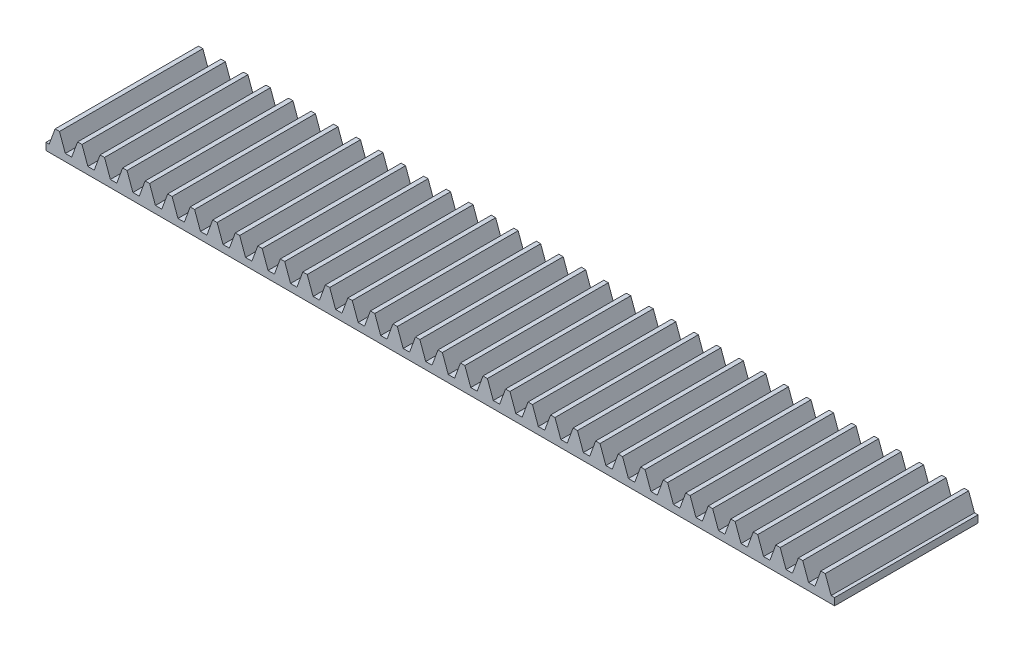
SolidWorks part; units mm, degrees
extrude "Blank" add sketch "BlankSke" against normal blind 20
sketch "BlankSke" plane through (0, 0, 0) normal (0, 0, 1) x (1, 0, 0)
  line L1 (0, 0) -> (110, 0)
  line L2 (0, 0) -> (0, 3.25)
  line L3 (0, 3.25) -> (110, 3.25)
  line L4 (110, 0) -> (110, 3.25)
  dimension "Length" = 110
  dimension "Blank_height" = 3.25
ref_plane "Plane1" through (0, 0, 0) normal (0, 0, 1) x (1, 0, 0)
ref_plane "Plane2" through (0, 0, 0) normal (0, 1, 0) x (1, 0, 0)
ref_plane "Plane3" through (0, 0, 0) normal (1, 0, 0) x (0, 0, -1)
other "Configuration Table"
sketch "HoldingSke" plane through (0, 0, 0) normal (0, 1, 0) x (1, 0, 0)
  line L0 (0, 0) -> (0.1392, 0.9903)
  line L1 (-15, 0) -> (100, 0) construction
  line L2 (0, 0) -> (-2.1039, 2.3779)
  line L3 (0, 0) -> (-11.863, 4.5341)
  line L4 (0, 0) -> (6.897, 5.1973)
  line L5 (0, 0) -> (-23.7986, -8.8762)
  line L6 (0, 0) -> (-10.5278, -7.1032)
  line L9 (-71.009, 38.7566) -> (32.3572, 76.3788)
  line L10 (-76.2, 3.3779) -> (-73.95, 3.3779)
  line L11 (0, 0) -> (-20, 0)
  line L12 (-76.2, 101.6) -> (-76.162, 101.6)
  line L13 (24.9733, 27.94) -> (52.9518, 28.4284)
  line L14 (24.9733, 27.94) -> (24.9743, 27.94)
  line L15 (24.9733, 27.94) -> (100.4006, 29.5858)
  circle A0 centre (0, 0) radius 19.05
  circle A1 centre (0, 0) radius 1.125
  circle A2 centre (0, 0) radius 12.7
  dimension "MPH" = 2.25
  dimension "Diameter" = 38.1
  dimension "Num_teeth" = 37
  dimension "Pitch" = 1
  dimension "Show_teeth" = 998
  dimension "Thickness" = 12.7
  dimension "Ap" = 20
  dimension "Pitch_height" = 2.25
  dimension "Width" = 20
  dimension "Backlash" = 0.038
  dimension "Addendum_fac" = 1
  dimension "Dedendum_fac" = 1.25
  dimension "Clearance_fac" = 0.25
  dimension "Dedendum_add" = 0.001
  dimension "Length" = 110
  dimension "Module" = 1
sketch "TooCutSkeIll" plane through (0, 0, 0) normal (0, 0, 1) x (1, 0, 0)
  line L0 (-1.2538, 3.2237) -> (-0.5045, 1.1652)
  line L1 (-0.2687, 1) -> (0.2687, 1)
  line L2 (0.5045, 1.1652) -> (1.2538, 3.2237)
  line L3 (110, 3.25) -> (0, 3.25) construction
  line L4 (0, 0) -> (0, 64.897) construction
  line L5 (-13.208, 2.25) -> (12.954, 2.25) construction
  line L6 (0, 0) -> (110, 0) construction
  line L7 (0.8994, 2.25) -> (0.8994, 48.7463) construction
  line L8 (-0.8994, 2.25) -> (-0.8994, 48.7463) construction
  line L9 (1.2914, 3.25) -> (1.2914, 3.2754)
  line L10 (-1.2914, 3.25) -> (-1.2914, 3.2754)
  line L11 (-1.2914, 3.2754) -> (1.2914, 3.2754)
  arc A0 (0.2687, 1) -> (0.5045, 1.1652) centre (0.2687, 1.251) ccw
  arc A1 (-0.5045, 1.1652) -> (-0.2687, 1) centre (-0.2687, 1.251) ccw
  arc A2 (1.2914, 3.25) -> (1.2538, 3.2237) centre (1.2914, 3.21) ccw
  arc A3 (-1.2538, 3.2237) -> (-1.2914, 3.25) centre (-1.2914, 3.21) ccw
  dimension "Pitch_height" = 2.25
  dimension "Addendum_plus" = 1.0254
  dimension "Pressure_angle" = 20
  dimension "Gap_width" = 1.7988
  dimension "Dedendum" = 1.25
extrude "ToothCutIll" [suppressed] cut sketch "TooCutSkeIll" against normal through all
sketch "TooCutSkeSim" plane through (0, 0, 0) normal (0, 0, 1) x (1, 0, 0)
  line L0 (0.4444, 1) -> (-0.4444, 1)
  line L1 (1.2726, 3.2754) -> (0.4444, 1)
  line L2 (0, 17.4625) -> (0, 53.467) construction
  line L3 (1.2726, 3.2754) -> (-1.2726, 3.2754)
  line L6 (-1.2726, 3.2754) -> (-0.4444, 1)
  line L9 (-0.8994, 2.25) -> (0.8994, 2.25) construction
  line L10 (0, 0) -> (110, 0) construction
  line L11 (0.8994, 2.25) -> (0.8994, 53.467) construction
  line L12 (-0.8994, 2.25) -> (-0.8994, 53.467) construction
  dimension "Pitch_height" = 2.25
  dimension "Addendum_plus" = 1.0254
  dimension "Pressure_angle" = 20
  dimension "Gap_width" = 1.7988
  dimension "Dedendum" = 1.25
extrude "ToothCutSim" cut sketch "TooCutSkeSim" against normal through all
pattern_linear "TeethCuts" count 36 spacing 3.1416 along (1, 0, 0) of "ToothCutIll", "ToothCutSim"
equation "' \"Module@HoldingSke\" = 6.35"
equation "' \"Num_teeth@HoldingSke\" = 12"
equation "' \"Ap@HoldingSke\" =  20"
equation "' \"Ap@HoldingSke\" = 20"
equation "' \"Width@HoldingSke\" = 0.25 * 25.4"
equation "' \"Show_teeth@HoldingSke\" = 500"
equation "' \"Backlash@HoldingSke\" = 0.009 * 25.4"
equation "' \"Addendum_fac@HoldingSke\" = 1.0"
equation "' \"Dedendum_fac@HoldingSke\" = 1.25"
equation "' \"Dedendum_add@HoldingSke\" = 0.00005 * 25.4"
equation "' \"Clearance_fac@HoldingSke\" = 0.25"
equation "' \"Pitch_height@HoldingSke\" = 1 * 25.4"
equation "' \"Length@HoldingSke\" = 4.71 * 25.4"
equation "\"Pitch@HoldingSke\" = 1 / \"Module@HoldingSke\""
equation "\"MPH@HoldingSke\" = \"Dedendum_fac@HoldingSke\" / \"Pitch@HoldingSke\" + 2 * \"Dedendum_add@HoldingSke\" + 0.002 * 25.4"
equation "\"MPH@HoldingSke\" = ((sgn( \"MPH@HoldingSke\" - \"Pitch_height@HoldingSke\")+1)*( \"MPH@HoldingSke\" - \"Pitch_height@HoldingSke\"))/2 + \"Pitch_height@HoldingSke\""
equation "\"Blank_height@BlankSke\" = \"Pitch_height@HoldingSke\" + \"Addendum_fac@HoldingSke\"  / \"Pitch@HoldingSke\" "
equation "\"Length@BlankSke\" =  \"Length@HoldingSke\""
equation "\"Face_width@Blank\" = \"Width@HoldingSke\""
equation "\"Pressure_angle@TooCutSkeIll\" = \"Ap@HoldingSke\""
equation "\"Addendum_plus@TooCutSkeIll\" =  \"Addendum_fac@HoldingSke\"  / \"Pitch@HoldingSke\" + 0.001 *25.4"
equation "\"Dedendum@TooCutSkeIll\" = \"Dedendum_fac@HoldingSke\"  / \"Pitch@HoldingSke\""
equation "\"Pitch_height@TooCutSkeIll\" =  \"MPH@HoldingSke\""
equation "\"Gap_width@TooCutSkeIll\" = 3.14159265 / 2 / \"Pitch@HoldingSke\" + 6 * \"Backlash@HoldingSke\""
equation "\"Pressure_angle@TooCutSkeSim\" = \"Ap@HoldingSke\""
equation "\"Addendum_plus@TooCutSkeSim\" =  \"Addendum_fac@HoldingSke\"  / \"Pitch@HoldingSke\" + 0.001 * 25.4"
equation "\"Dedendum@TooCutSkeSim\" = \"Dedendum_fac@HoldingSke\"  / \"Pitch@HoldingSke\""
equation "\"Pitch_height@TooCutSkeSim\" =  \"MPH@HoldingSke\""
equation "\"Gap_width@TooCutSkeSim\" = 3.14159265 / 2 / \"Pitch@HoldingSke\" + 6 * \"Backlash@HoldingSke\""
equation "\"Root_fillet@TooCutSkeIll\" = \"Clearance_fac@HoldingSke\" / \"Pitch@HoldingSke\" + \"Dedendum_add@HoldingSke\""
equation "\"Break_rad@TooCutSkeIll\" = 0.02 / \"Pitch@HoldingSke\" * 2"
equation "\"Linear_pitch@TeethCuts\" = 3.14159265 / \"Pitch@HoldingSke\""
equation "\"Num_teeth@HoldingSke\" = int( ( \"Length@HoldingSke\" + 0 ) / (3.14159265 / \"Pitch@HoldingSke\")) + 0.9999  + 1"
equation " \"Num_teeth@TeethCuts\" = int( \"Show_teeth@HoldingSke\" ) + 1"
equation " \"Num_teeth@TeethCuts\" = ((sgn( \"Num_teeth@TeethCuts\" - \"Num_teeth@HoldingSke\" )-1)*( \"Num_teeth@TeethCuts\" - \"Num_teeth@HoldingSke\" ))/-2+ \"Num_teeth@HoldingSke\""
equation " \"Num_teeth@TeethCuts\" = ((sgn( \"Num_teeth@TeethCuts\" - 2.0)+1)*( \"Num_teeth@TeethCuts\" - 2.0))/2 +2.0"
